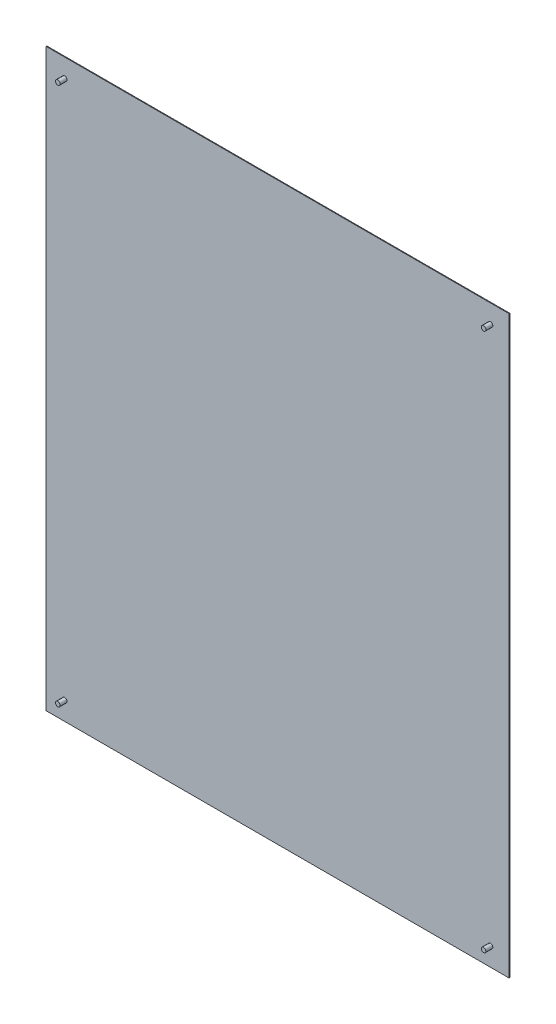
SolidWorks part; units mm, degrees
ref_plane "Front Plane" through (0, 0, 0) normal (0, 0, 1) x (1, 0, 0)
ref_plane "Top Plane" through (0, 0, 0) normal (0, 1, 0) x (1, 0, 0)
ref_plane "Right Plane" through (0, 0, 0) normal (1, 0, 0) x (0, 0, -1)
sketch "Sketch1" plane through (0, 0, 0) normal (0, 0, 1) x (1, 0, 0)
  line L1 (317.5, 394.716) -> (-317.5, 394.716)
  line L2 (317.5, 394.716) -> (317.5, -394.716)
  line L3 (317.5, -394.716) -> (-317.5, -394.716)
  line L4 (-317.5, 394.716) -> (-317.5, -394.716)
  line L5 (317.5, 394.716) -> (-317.5, -394.716) construction
  line L6 (317.5, -394.716) -> (-317.5, 394.716) construction
  point P0 (0, 0)
  dimension "D1" = 635
  dimension "D2" = 789.432
extrude "Boss-Extrude1" add sketch "Sketch1" along normal blind 1 contours L4 L3 L2 L1
sketch "Sketch2" plane through (0, 0, 1) normal (0, 0, 1) x (1, 0, 0)
  line L0 (317.5, 394.716) -> (-317.5, 394.716) construction
  line L1 (-317.5, 394.716) -> (-317.5, -394.716) construction
  line L2 (0, 0) -> (0, 394.716) construction
  line L3 (0, 0) -> (317.5, 0) construction
  line L4 (317.5, 394.716) -> (317.5, -394.716) construction
  circle A0 centre (-292.1, 369.316) radius 3.175
  circle A1 centre (292.1, 369.316) radius 3.175
  circle A2 centre (-292.1, -369.316) radius 3.175
  circle A3 centre (292.1, -369.316) radius 3.175
  dimension "D1" = 6.35
  dimension "D2" = 25.4
  dimension "D3" = 25.4
extrude "Boss-Extrude2" add sketch "Sketch2" along normal mid plane 19.05
